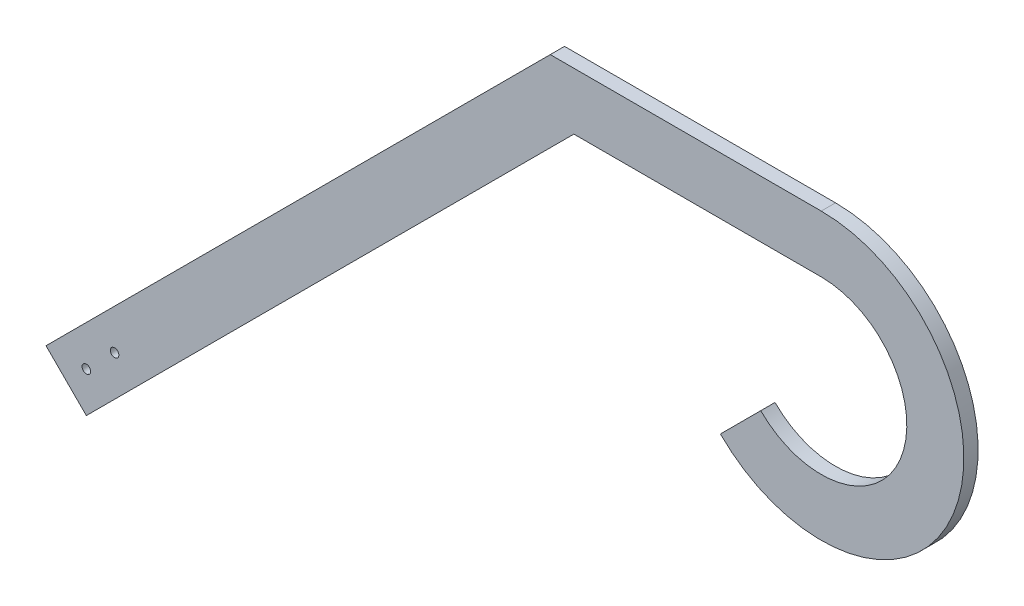
SolidWorks part; units mm, degrees
material "冷拉钢丝 45"
ref_plane "前视基准面" through (0, 0, 0) normal (0, 0, 1) x (1, 0, 0)
ref_plane "上视基准面" through (0, 0, 0) normal (0, 1, 0) x (1, 0, 0)
ref_plane "右视基准面" through (0, 0, 0) normal (1, 0, 0) x (0, 0, -1)
sketch "草图1" plane through (0, 0, 0) normal (0, 0, 1) x (1, 0, 0)
  line L0 (0, 50) -> (-95, 50)
  line L1 (-95, 50) -> (-271.7767, -126.7767)
  line L2 (-271.7767, -126.7767) -> (-257.6346, -140.9188)
  line L3 (0, 30) -> (-86.7157, 30)
  line L4 (-86.7157, 30) -> (-257.6346, -140.9188)
  line L5 (-21.2132, -21.2132) -> (-35.3553, -35.3553)
  arc A0 (-35.3553, -35.3553) -> (0, 50) centre (0, 0) ccw
  arc A1 (-21.2132, -21.2132) -> (0, 30) centre (0, 0) ccw
  dimension "D1" = 100
  dimension "D3" = 95
  dimension "D4" = 250
  dimension "D5" = 135
  dimension "D7" = 45
  dimension "D6" = 20
extrude "凸台-拉伸1" add sketch "草图1" along normal blind 5
sketch "草图2" plane through (0, 0, 5) normal (0, 0, 1) x (1, 0, 0)
  line L0 (-264.7056, -133.8478) -> (-238.5328, -107.6749) construction
  line L1 (-271.7767, -126.7767) -> (-257.6346, -140.9188) construction
  circle A0 centre (-257.6346, -126.7767) radius 1.5
  circle A1 centre (-247.7351, -116.8772) radius 1.5
  dimension "D1" = 3
  dimension "D2" = 3
  dimension "D3" = 10
  dimension "D4" = 14
extrude "切除-拉伸1" cut sketch "草图2" against normal through all
